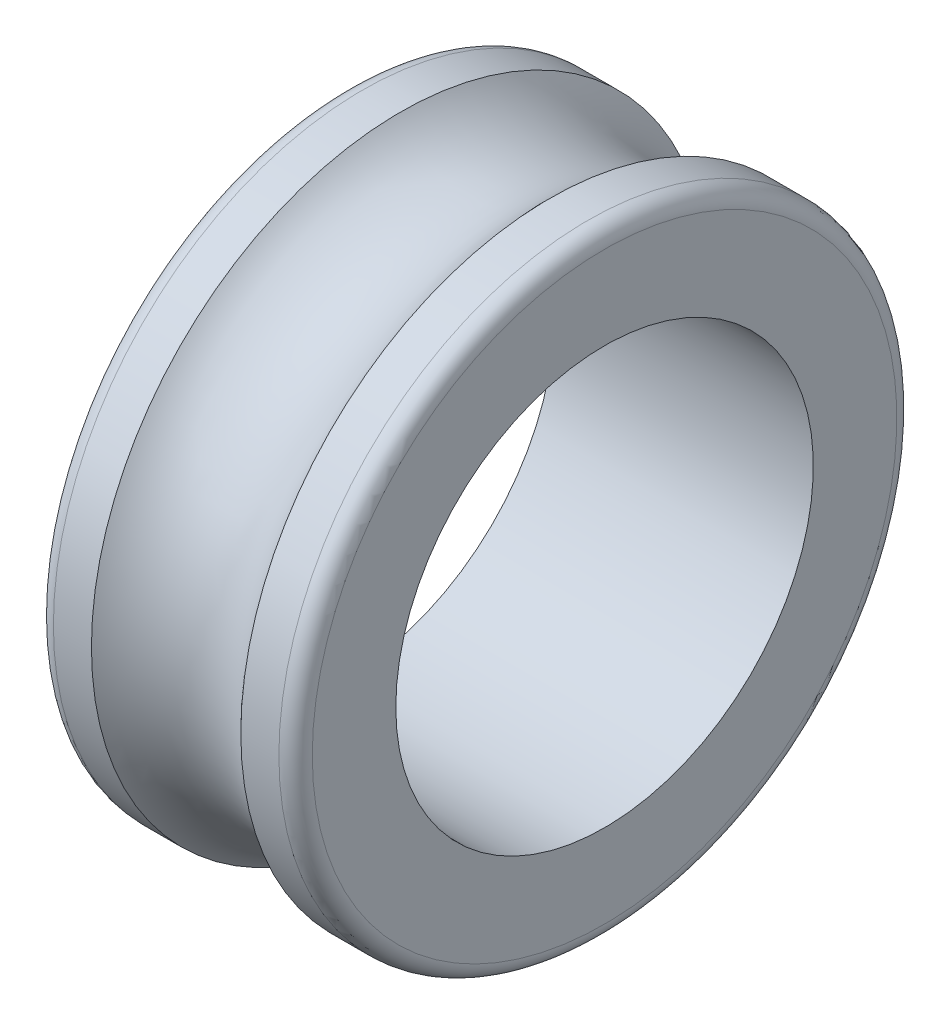
SolidWorks part; units mm, degrees
ref_plane "Front Plane" through (0, 0, 0) normal (0, 0, 1) x (1, 0, 0)
ref_plane "Top Plane" through (0, 0, 0) normal (0, 1, 0) x (1, 0, 0)
ref_plane "Right Plane" through (0, 0, 0) normal (1, 0, 0) x (0, 0, -1)
sketch "Sketch1" plane through (0, 0, 0) normal (0, 0, 1) x (1, 0, 0)
  line L0 (0, 0) -> (35449.0872, 0) construction
  line L1 (0, 0) -> (0, -35449.0872) construction
  line L2 (8.9443, 37) -> (13.5, 37)
  line L3 (-13.5, 37) -> (-8.9443, 37)
  line L4 (-15.5, 35) -> (-15.5, 25)
  line L5 (-15.5, 25) -> (15.5, 25)
  line L6 (15.5, 35) -> (15.5, 25)
  line L7 (-15.5, 37) -> (15.5, 25) construction
  line L8 (-15.5, 25) -> (15.5, 37) construction
  arc A0 (-8.9443, 37) -> (8.9443, 37) centre (0, 45) ccw
  arc A1 (13.5, 37) -> (15.5, 35) centre (13.5, 35) cw
  arc A2 (-13.5, 37) -> (-15.5, 35) centre (-13.5, 35) ccw
  point P5 (0, 31)
  dimension "D4" = 12
  dimension "D6" = 2
  dimension "D1" = 50
  dimension "D2" = 74
  dimension "D3" = 31
  dimension "D5" = 8
revolve "Revolve1" add sketch "Sketch1" angle 360 about L0
